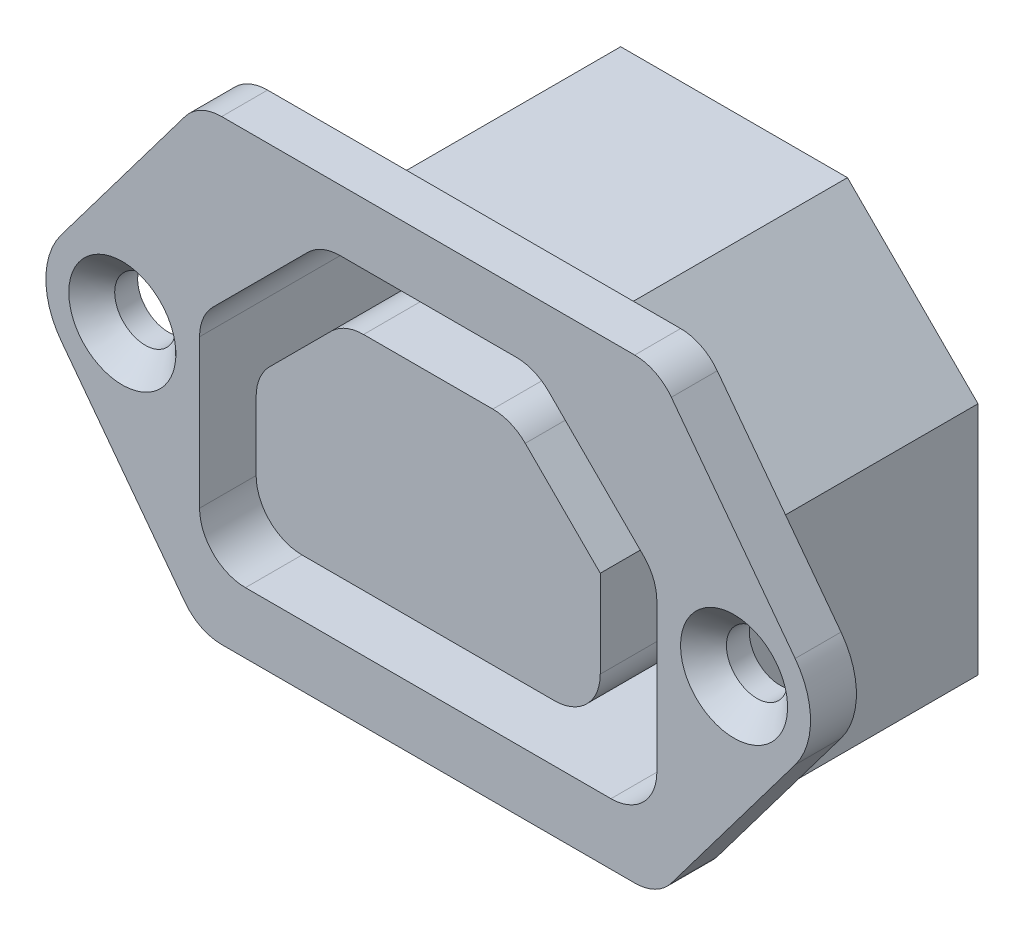
SolidWorks part; units mm, degrees
ref_plane "Front Plane" through (0, 0, 0) normal (0, 0, 1) x (1, 0, 0)
ref_plane "Top Plane" through (0, 0, 0) normal (0, 1, 0) x (1, 0, 0)
ref_plane "Right Plane" through (0, 0, 0) normal (1, 0, 0) x (0, 0, -1)
sketch "Sketch1" plane through (0, 0, 0) normal (0, 0, 1) x (1, 0, 0)
  line L0 (0, 56.9009) -> (0, -65.5045) construction
  line L1 (-84.4714, 0) -> (78.0187, 0) construction
  line L2 (-14.95, 3) -> (-7, 10.95)
  line L3 (14.95, -10.95) -> (-14.95, -10.95)
  line L4 (14.95, -10.95) -> (14.95, 3)
  line L5 (7, 10.95) -> (-7, 10.95)
  line L6 (-14.95, -10.95) -> (-14.95, 3)
  line L7 (14.95, -10.95) -> (-10.3611, 7.5889) construction
  line L8 (10.3611, 7.5889) -> (-14.95, -10.95) construction
  line L9 (14.95, 3) -> (7, 10.95)
  line L16 (-23.994, -3.008) -> (-15, -14.95)
  line L17 (-23.994, 3.008) -> (-15, 14.95)
  line L18 (-15, 14.95) -> (15, 14.95)
  line L19 (-15, -14.95) -> (15, -14.95)
  line L20 (23.994, -3.008) -> (15, -14.95)
  line L21 (23.994, 3.008) -> (15, 14.95)
  circle A0 centre (-20, 0) radius 2
  circle A1 centre (20, 0) radius 2
  arc A2 (-23.994, -3.008) -> (-23.994, 3.008) centre (-20, 0) cw
  arc A3 (23.994, -3.008) -> (23.994, 3.008) centre (20, 0) ccw
  point P5 (0, 0)
  point P22 (0, 0)
  point P23 (-25, 0)
  point P27 (0, -14.95)
  point P31 (0, 14.95)
  point P32 (-23.4519, 3.8663)
  point P33 (0, 0)
  dimension "D6" = 4
  dimension "D1" = 21.9
  dimension "D2" = 29.9
  dimension "D3" = 45
  dimension "D4" = 7
  dimension "D5" = 13.95
  dimension "D7" = 40
  dimension "D8" = 21.9
  dimension "D9" = 4
  dimension "D10" = 50
  dimension "D11" = 30
  dimension "D12" = 29.9
  dimension "D13" = 30
extrude "Boss-Extrude1" add sketch "Sketch1" along normal mid plane 3
sketch "Sketch2" plane through (0, 0, -1.5) normal (0, 0, -1) x (-1, 0, 0)
  line L0 (14.95, -10.95) -> (-14.95, -10.95) construction
  line L1 (14.95, 3) -> (14.95, -10.95) construction
  line L2 (7, 10.95) -> (14.95, 3) construction
  line L3 (-7, 10.95) -> (7, 10.95) construction
  line L4 (-14.95, -10.95) -> (-14.95, 3) construction
  line L5 (-14.95, 3) -> (-7, 10.95) construction
  line L6 (14.95, -10.95) -> (-14.95, -10.95)
  line L7 (14.95, 3) -> (14.95, -10.95)
  line L8 (7, 10.95) -> (14.95, 3)
  line L9 (-7, 10.95) -> (7, 10.95)
  line L10 (-14.95, -10.95) -> (-14.95, 3)
  line L11 (-14.95, 3) -> (-7, 10.95)
  line L12 (-11.25, 1.4674) -> (-5.4674, 7.25)
  line L13 (-5.4674, 7.25) -> (5.4674, 7.25)
  line L14 (5.4674, 7.25) -> (11.25, 1.4674)
  line L15 (11.25, 1.4674) -> (11.25, -7.25)
  line L16 (11.25, -7.25) -> (-11.25, -7.25)
  line L17 (-11.25, -7.25) -> (-11.25, 1.4674)
  line L18 (-15.95, 3.4142) -> (-7.4142, 11.95)
  line L19 (-7.4142, 11.95) -> (7.4142, 11.95)
  line L20 (7.4142, 11.95) -> (15.95, 3.4142)
  line L21 (15.95, 3.4142) -> (15.95, -11.95)
  line L22 (15.95, -11.95) -> (-15.95, -11.95)
  line L23 (-15.95, -11.95) -> (-15.95, 3.4142)
  dimension "D3" = 31.9
  dimension "D1" = 3.7
  dimension "D2" = 1
extrude "Boss-Extrude2" add sketch "Sketch2" along normal blind 17 and the other way up to surface contours L6 L10 L11 L9 L8 L7 | L22 L23 L18 L19 L20 L21 | L16 L17 L12 L13 L14 L15
sketch "Sketch3" plane through (0, 0, -18.5) normal (0, 0, -1) x (-1, 0, 0)
  line L12 (15.95, -11.95) -> (15.95, 3.4142)
  line L13 (15.95, 3.4142) -> (7.4142, 11.95)
  line L14 (7.4142, 11.95) -> (-7.4142, 11.95)
  line L15 (-7.4142, 11.95) -> (-15.95, 3.4142)
  line L16 (-15.95, 3.4142) -> (-15.95, -11.95)
  line L17 (-15.95, -11.95) -> (15.95, -11.95)
  line L18 (15.95, -11.95) -> (15.95, 3.4142)
  line L19 (15.95, 3.4142) -> (7.4142, 11.95)
  line L20 (7.4142, 11.95) -> (-7.4142, 11.95)
  line L21 (-7.4142, 11.95) -> (-15.95, 3.4142)
  line L22 (-15.95, 3.4142) -> (-15.95, -11.95)
  line L23 (-15.95, -11.95) -> (15.95, -11.95)
  dimension "D1" = 0
extrude "Boss-Extrude3" add sketch "Sketch3" against normal blind 1
chamfer "Chamfer1" distance 1.5 angle 45 2 edges at (18, 0, 1.5) (-18, 0, 1.5)
fillet "Fillet1" radius 3 15 edges at (15, -14.95, 0) (-15, -14.95, 0) (-15, 14.95, 0) (15, 14.95, 0) (11.25, -7.25, -8) (-11.25, -7.25, -8) (-11.25, 1.4674, -8) (-5.4674, 7.25, -8) (5.4674, 7.25, -8) (14.95, -10.95, -8) (14.95, 3, -8) (7, 10.95, -8) (-7, 10.95, -8) (-14.95, 3, -8) (-14.95, -10.95, -8)
